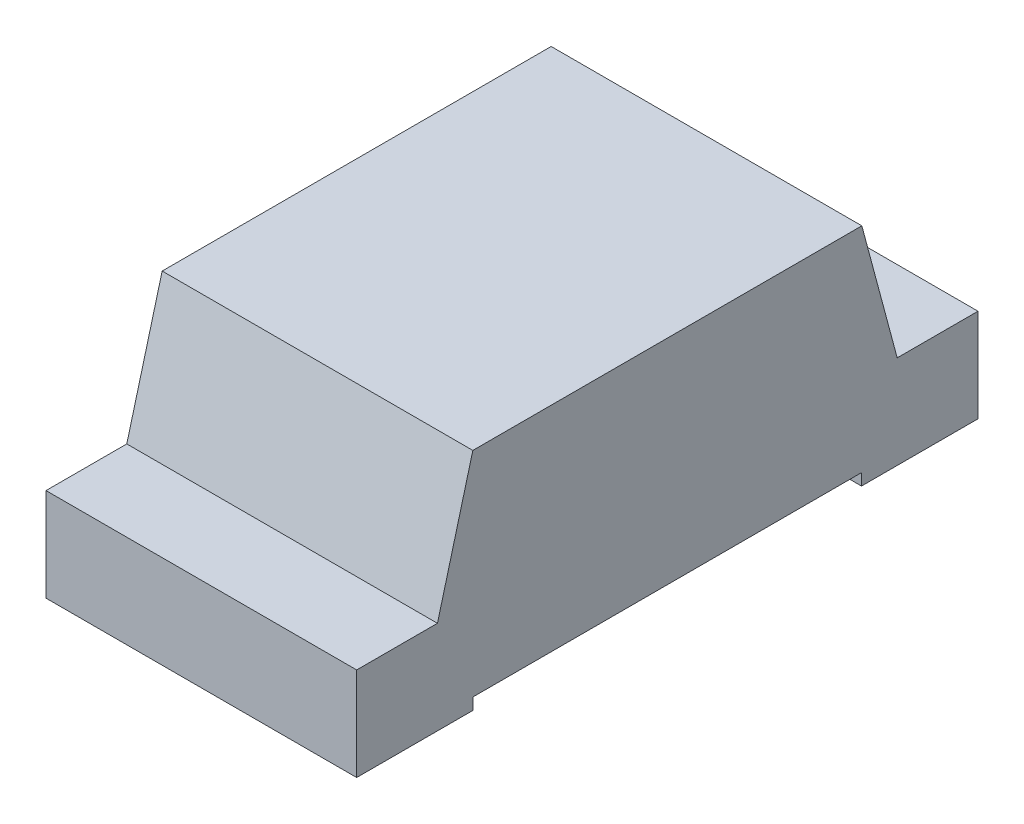
SolidWorks part; units mm, degrees
ref_plane "Front" through (0, 0, 0) normal (0, 0, 1) x (1, 0, 0)
ref_plane "Top" through (0, 0, 0) normal (0, 1, 0) x (1, 0, 0)
ref_plane "Right" through (0, 0, 0) normal (1, 0, 0) x (0, 0, -1)
sketch "Sketch2" plane through (0, 0, 0) normal (1, 0, 0) x (0, 0, -1)
  line L0 (0.5, 0.03) -> (-0.5, 0.03)
  line L1 (0.5, 0.03) -> (0.5, 0)
  line L2 (0.5, 0) -> (0.8, 0)
  line L3 (0.8, 0) -> (0.8, 0.24)
  line L4 (0.8, 0.24) -> (0.592, 0.24)
  line L5 (0.592, 0.24) -> (0.5009, 0.58)
  line L6 (0.5009, 0.58) -> (-0.5009, 0.58)
  line L7 (0, -0.2958) -> (0, 0.9617) construction
  line L8 (-0.592, 0.24) -> (-0.5009, 0.58)
  line L9 (-0.8, 0.24) -> (-0.592, 0.24)
  line L10 (-0.8, 0) -> (-0.8, 0.24)
  line L11 (-0.5, 0) -> (-0.8, 0)
  line L12 (-0.5, 0.03) -> (-0.5, 0)
  line L13 (0.592, 0.24) -> (0.6, 0.21) construction
  line L14 (0.6, 0.21) -> (0.8, 0.21) construction
  dimension "D1" = 0.03
  dimension "D2" = 0.03
  dimension "D3" = 0.18
  dimension "D4" = 15
  dimension "D5" = 0.55
  dimension "D6" = 1.2
  dimension "D7" = 1.6
  dimension "D8" = 1
extrude "Boss-Extrude1" add sketch "Sketch2" along normal mid plane 0.8
